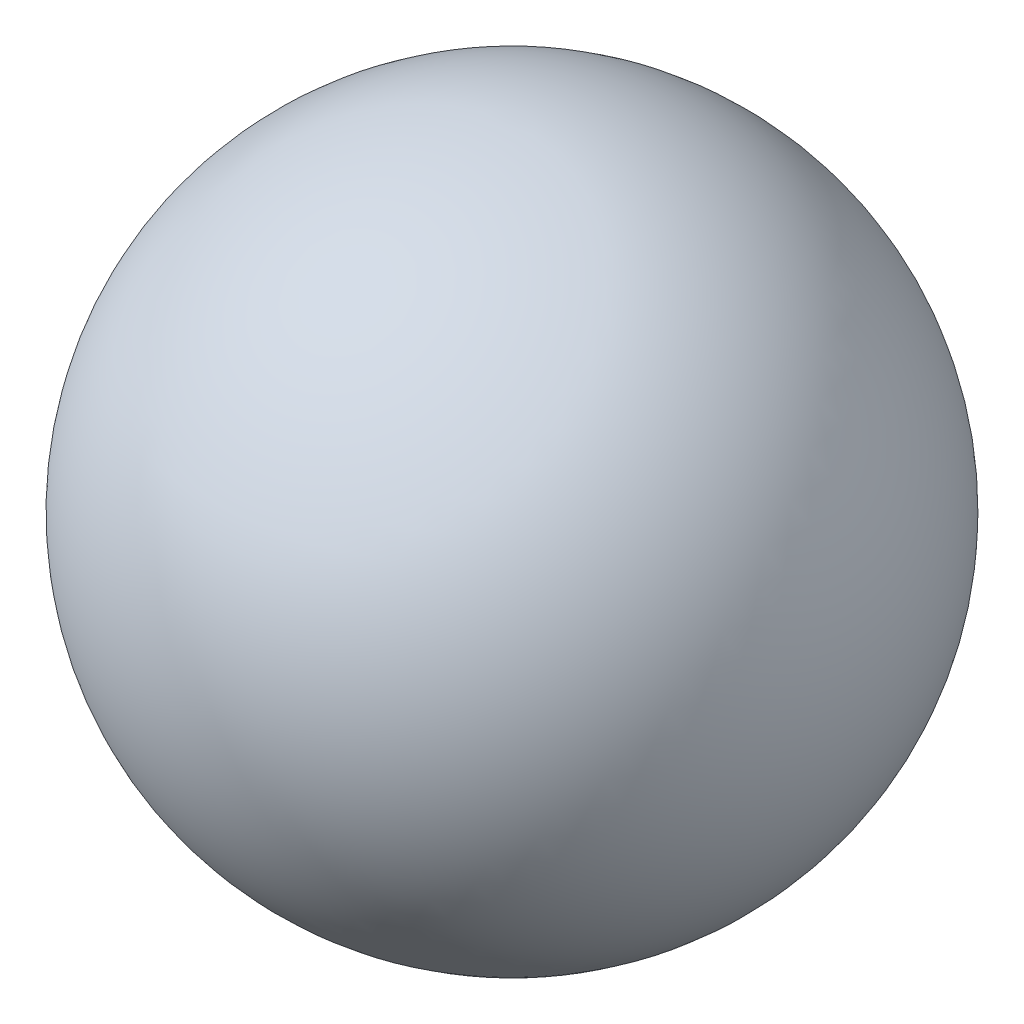
SolidWorks part; units mm, degrees
ref_plane "Plano frontal" through (0, 0, 0) normal (0, 0, 1) x (1, 0, 0)
ref_plane "Plano superior" through (0, 0, 0) normal (0, 1, 0) x (1, 0, 0)
ref_plane "Plano direito" through (0, 0, 0) normal (1, 0, 0) x (0, 0, -1)
sketch "Esboço1" plane through (0, 0, 0) normal (0, 0, 1) x (1, 0, 0)
  line L0 (2.2808, -74.9653) -> (-2.2808, 74.9653)
  arc A0 (-2.2808, 74.9653) -> (2.2808, -74.9653) centre (0, 0) ccw
  point P6 (0, 0)
  dimension "D1" = 150
revolve "Revolução1" add sketch "Esboço1" angle 360 about L0
